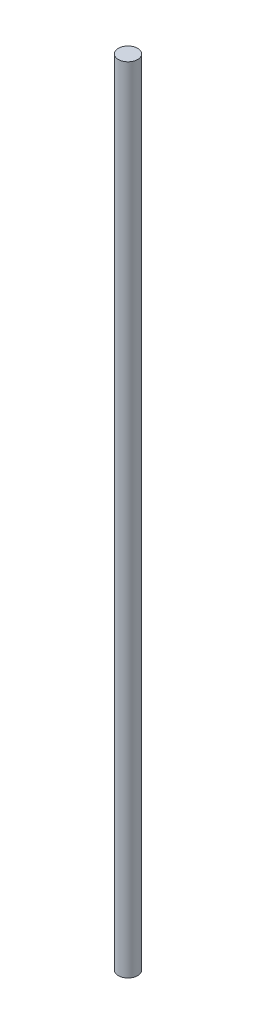
SolidWorks part; units mm, degrees
ref_plane "Front Plane" through (0, 0, 0) normal (0, 0, 1) x (1, 0, 0)
ref_plane "Top Plane" through (0, 0, 0) normal (0, 1, 0) x (1, 0, 0)
ref_plane "Right Plane" through (0, 0, 0) normal (1, 0, 0) x (0, 0, -1)
sketch "Sketch1" plane through (0, 0, 0) normal (0, 1, 0) x (1, 0, 0)
  circle A0 centre (0, 0) radius 3.175
  dimension "D1" = 6.35
extrude "Boss-Extrude1" add sketch "Sketch1" along normal blind 260.35 contours A0
equation "\"L\"= \"RodLength@J3Rod.Assembly\""
equation "\"D1@Boss-Extrude1\"=\"RodMax\""
equation "\"centerBotDist\"= 5 / 8"
equation "\"RodMax\"= \"L\" - 2 * \"centerBotDist\""
equation "\"Wiggle\"= .125"
equation "\"ThreadRodLength\"= \"RodMax\" - \"Wiggle\""
